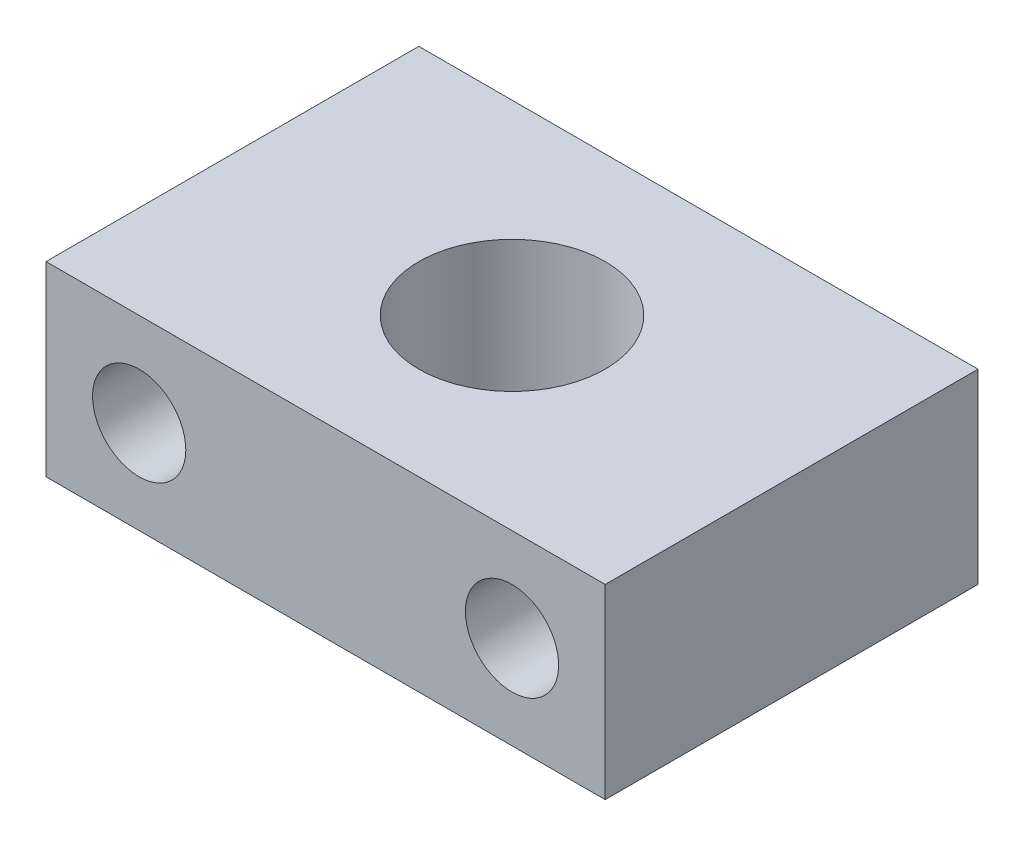
SolidWorks part; units mm, degrees
material "6061 Alloy"
ref_plane "Front Plane" through (0, 0, 0) normal (0, 0, 1) x (1, 0, 0)
ref_plane "Top Plane" through (0, 0, 0) normal (0, 1, 0) x (1, 0, 0)
ref_plane "Right Plane" through (0, 0, 0) normal (1, 0, 0) x (0, 0, -1)
sketch "Sketch1" plane through (0, 0, 0) normal (0, 1, 0) x (1, 0, 0)
  line L1 (-19.05, 12.7) -> (19.05, 12.7)
  line L2 (-19.05, 12.7) -> (-19.05, -12.7)
  line L3 (-19.05, -12.7) -> (19.05, -12.7)
  line L4 (19.05, 12.7) -> (19.05, -12.7)
  line L5 (-19.05, 12.7) -> (19.05, -12.7) construction
  line L6 (-19.05, -12.7) -> (19.05, 12.7) construction
  point P0 (0, 0)
  dimension "D1" = 38.1
  dimension "D2" = 25.4
extrude "Boss-Extrude1" add sketch "Sketch1" along normal blind 12.7
sketch "Sketch2" plane through (0, 12.7, 0) normal (0, 1, 0) x (1, 0, 0)
  circle A0 centre (0, 0) radius 6.35
  dimension "D1" = 12.7
extrude "Cut-Extrude1" cut sketch "Sketch2" against normal through all
sketch "Sketch3" plane through (0, 0, -12.7) normal (0, 0, -1) x (-1, 0, 0)
  line L0 (0, 12.7) -> (0, 0) construction
  line L1 (-19.05, 12.7) -> (19.05, 12.7) construction
  line L2 (-19.05, 6.35) -> (19.05, 6.35) construction
  line L3 (-19.05, 12.7) -> (-19.05, 0) construction
  line L4 (19.05, 12.7) -> (19.05, 0) construction
  line L5 (-19.05, 0) -> (19.05, 0) construction
  circle A0 centre (-12.7, 6.35) radius 3.175
  circle A1 centre (12.7, 6.35) radius 3.175
  dimension "D1" = 6.35
  dimension "D2" = 6.35
  dimension "D3" = 6.35
extrude "Cut-Extrude2" cut sketch "Sketch3" against normal through all
